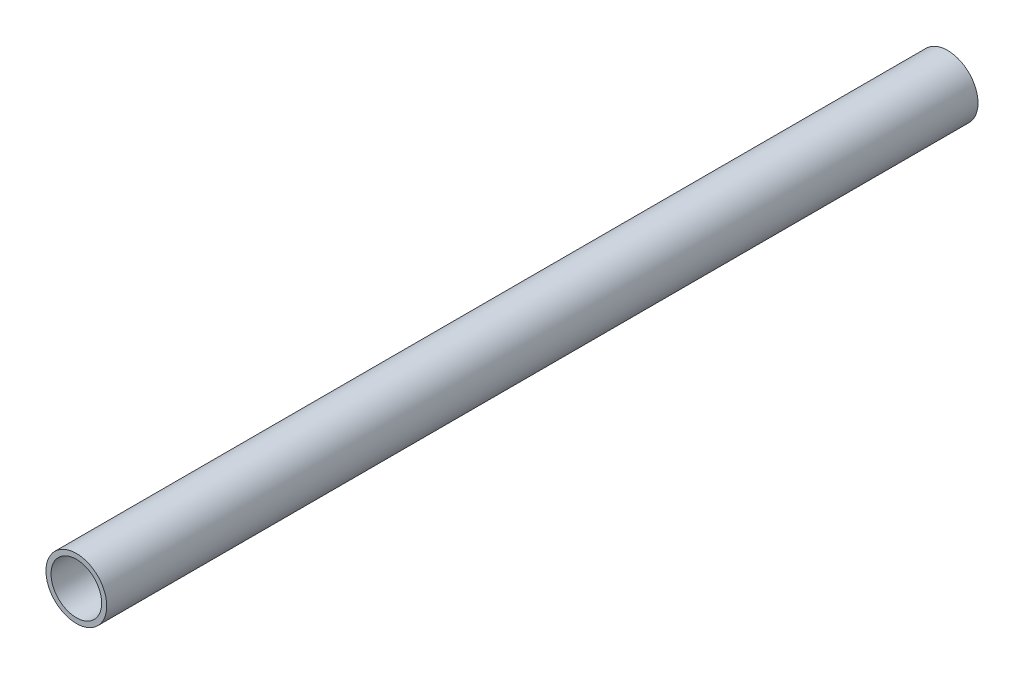
SolidWorks part; units mm, degrees
ref_plane "Front Plane" through (0, 0, 0) normal (0, 0, 1) x (1, 0, 0)
ref_plane "Top Plane" through (0, 0, 0) normal (0, 1, 0) x (1, 0, 0)
ref_plane "Right Plane" through (0, 0, 0) normal (1, 0, 0) x (0, 0, -1)
sketch "Sketch1" plane through (0, 0, 0) normal (0, 0, 1) x (1, 0, 0)
  circle A0 centre (0, 0) radius 6
  circle A1 centre (0, 0) radius 5
  dimension "D1" = 12
  dimension "D2" = 10
extrude "Boss-Extrude1" add sketch "Sketch1" along normal blind 172
